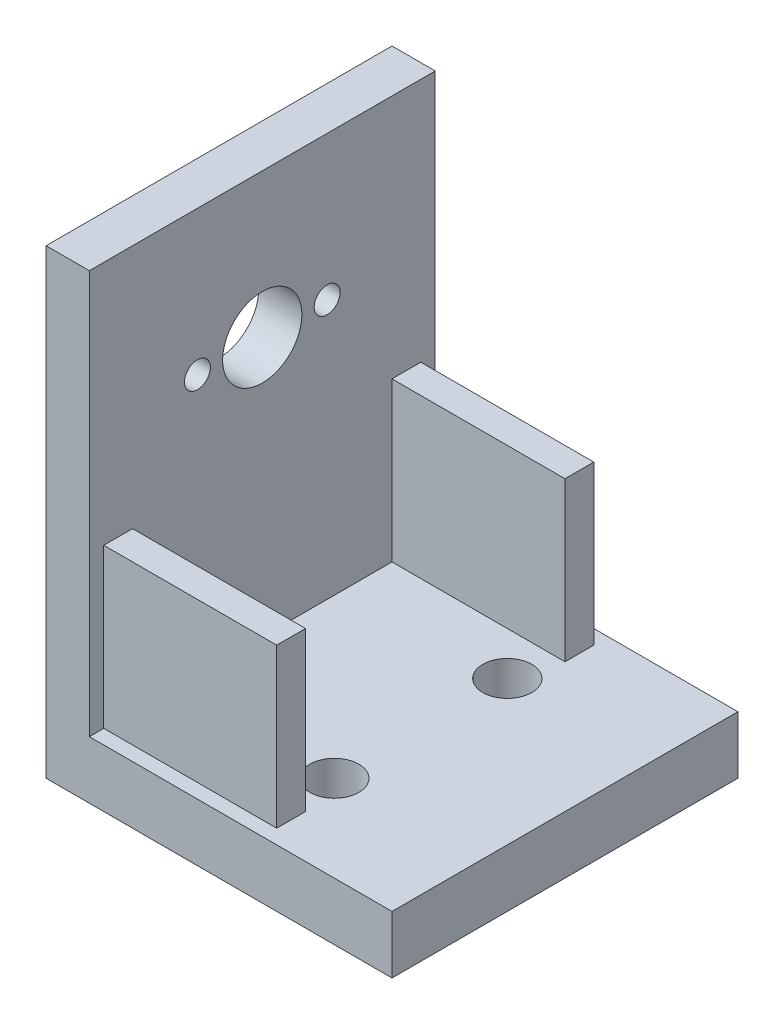
SolidWorks part; units mm, degrees
ref_plane "Front Plane" through (0, 0, 0) normal (0, 0, 1) x (1, 0, 0)
ref_plane "Top Plane" through (0, 0, 0) normal (0, 1, 0) x (1, 0, 0)
ref_plane "Right Plane" through (0, 0, 0) normal (1, 0, 0) x (0, 0, -1)
sketch "Sketch1" plane through (0, 0, 0) normal (0, 1, 0) x (1, 0, 0)
  line L1 (-12, -12) -> (12, -12)
  line L2 (-12, -12) -> (-12, 12)
  line L3 (-12, 12) -> (12, 12)
  line L4 (12, -12) -> (12, 12)
  line L5 (-12, -12) -> (12, 12) construction
  line L6 (-12, 12) -> (12, -12) construction
  point P0 (0, 0)
extrude "Boss-Extrude1" add sketch "Sketch1" along normal blind 4
sketch "Sketch2" plane through (0, 4, 0) normal (0, 1, 0) x (1, 0, 0)
  line L1 (-12, 12) -> (-9, 12)
  line L2 (-12, 12) -> (-12, -12)
  line L3 (-12, -12) -> (-9, -12)
  line L4 (-9, 12) -> (-9, -12)
extrude "Boss-Extrude2" add sketch "Sketch2" along normal blind 28
sketch "Sketch3" plane through (-9, 0, 0) normal (1, 0, 0) x (0, 0, -1)
  line L0 (12, 0) -> (12, 22) construction
  line L1 (12, 32) -> (12, 4) construction
  line L2 (12, 22) -> (0, 22) construction
  circle A0 centre (0, 22) radius 2.75
  circle A1 centre (4.5, 22) radius 0.9
  circle A2 centre (-4.5, 22) radius 0.9
  dimension "D1" = 22
  dimension "D3" = 4.5
  dimension "D2" = 12
  dimension "D4" = 4.5
extrude "Cut-Extrude1" cut sketch "Sketch3" against normal blind 3
sketch "Sketch4" plane through (0, 4, 0) normal (0, 1, 0) x (1, 0, 0)
  line L0 (-12, 12) -> (2, 12) construction
  line L1 (12, 12) -> (-9, 12) construction
  line L2 (2, 7.7) -> (2, 4.3) construction
  line L3 (2, 4.3) -> (2, 6)
  line L4 (2, -4.3) -> (2, -6)
  circle A0 centre (2, 6) radius 1.7
  circle A1 centre (2, -6) radius 1.7
  dimension "D1" = 3.4
  dimension "D2" = 12
  dimension "D3" = 14
extrude "Cut-Extrude2" cut sketch "Sketch4" against normal blind 4 contours A1 | A0
sketch "Sketch6" plane through (0, 4, 0) normal (0, 1, 0) x (1, 0, 0)
  line L0 (-9, -12) -> (-9, 12) construction
  line L1 (-9, -11) -> (3, -11)
  line L2 (-9, -11) -> (-9, -9)
  line L3 (-9, -9) -> (3, -9)
  line L4 (3, -11) -> (3, -9)
  line L5 (-9, -12) -> (12, -12) construction
  line L6 (13.8491, 0) -> (-22.3717, 0) construction
  line L7 (3, 11) -> (3, 9)
  line L8 (-9, 9) -> (3, 9)
  line L9 (-9, 11) -> (-9, 9)
  line L10 (-9, 11) -> (3, 11)
  dimension "D1" = 12
  dimension "D2" = 2
  dimension "D3" = 1
extrude "Boss-Extrude3" add sketch "Sketch6" along normal blind 11
